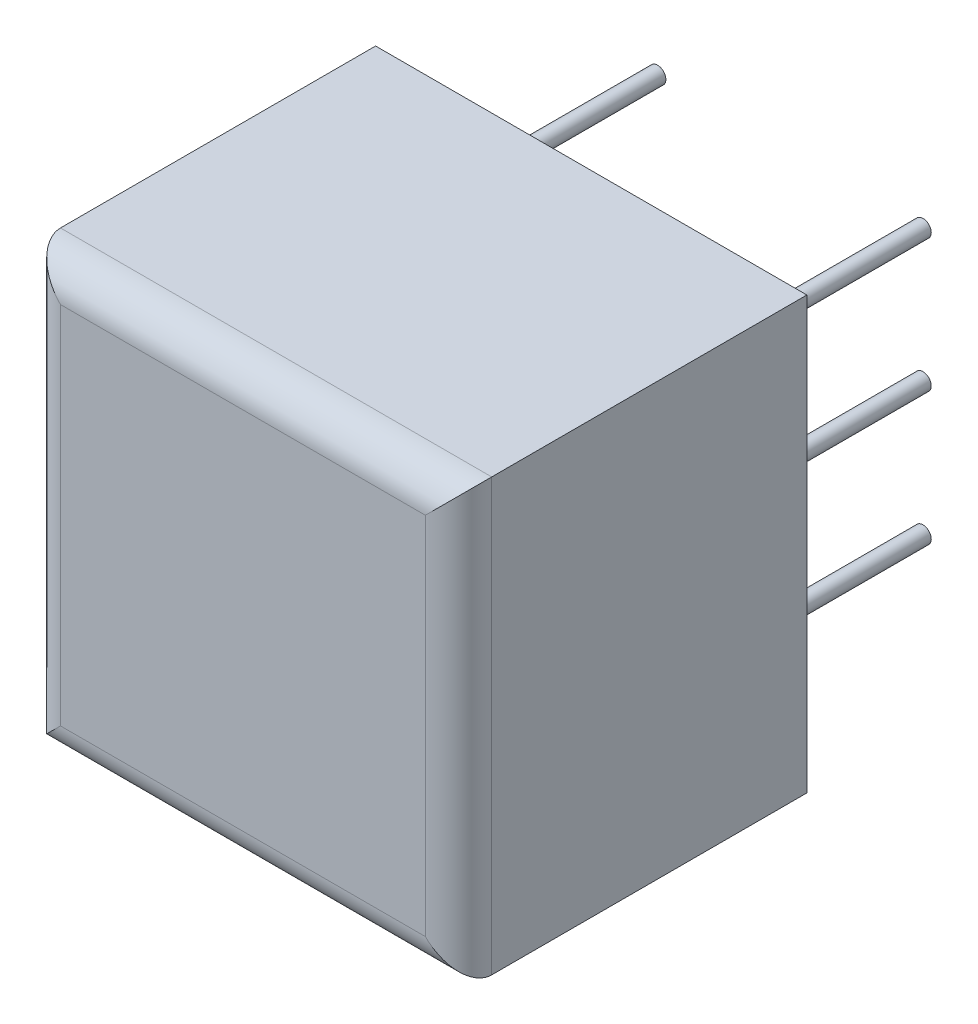
SolidWorks part; units mm, degrees
ref_plane "前视基准面" through (0, 0, 0) normal (0, 0, 1) x (1, 0, 0)
ref_plane "上视基准面" through (0, 0, 0) normal (0, 1, 0) x (1, 0, 0)
ref_plane "右视基准面" through (0, 0, 0) normal (1, 0, 0) x (0, 0, -1)
sketch "草图1" plane through (0, 0, 0) normal (0, 0, 1) x (1, 0, 0)
  line L0 (-39.8997, 0) -> (51.7253, 0) construction
  line L1 (-13, 13) -> (13, 13)
  line L2 (-13, 13) -> (-13, -13)
  line L3 (-13, -13) -> (13, -13)
  line L4 (13, 13) -> (13, -13)
  line L5 (0, 28.2891) -> (0, -33.3943) construction
  dimension "D1" = 26
  dimension "D2" = 26
extrude "凸台-拉伸1" add sketch "草图1" along normal blind 21
fillet "圆角1" radius 2 4 edges at (13, 0, 21) (0, 13, 21) (-13, 0, 21) (0, -13, 21)
sketch "草图2" plane through (0, 0, 0) normal (0, 0, -1) x (-1, 0, 0)
  line L0 (20.4299, 0) -> (-17.9183, 0) construction
  line L1 (0, 15.958) -> (0, -17.4895) construction
  line L2 (-8, 11.1185) -> (-8, -8.6069) construction
  circle A0 centre (-8, 8) radius 0.5
  circle A1 centre (-8, 0) radius 0.5
  circle A2 centre (-8, -8) radius 0.5
  circle A3 centre (8, -8) radius 0.5
  circle A4 centre (8, 8) radius 0.5
  dimension "D1" = 1
  dimension "D2" = 1
  dimension "D3" = 8
  dimension "D4" = 8
extrude "凸台-拉伸2" add sketch "草图2" along normal blind 12
